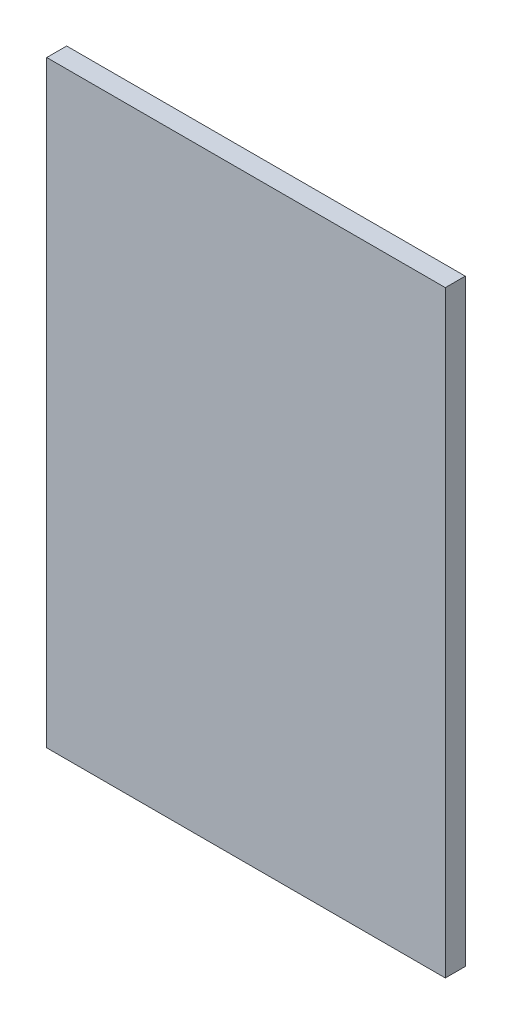
SolidWorks part; units mm, degrees
ref_plane "前视基准面" through (0, 0, 0) normal (0, 0, 1) x (1, 0, 0)
ref_plane "上视基准面" through (0, 0, 0) normal (0, 1, 0) x (1, 0, 0)
ref_plane "右视基准面" through (0, 0, 0) normal (1, 0, 0) x (0, 0, -1)
other "Configuration Table"
sketch "草图1" plane through (0, 0, 0) normal (0, 0, 1) x (1, 0, 0)
  line L0 (-20, -30) -> (20, -30)
  line L1 (20, -30) -> (20, 30)
  line L2 (20, 30) -> (-20, 30)
  line L3 (-20, 30) -> (-20, -30)
extrude "飞控减振垫_2mm占位" add sketch "草图1" along normal blind 2
